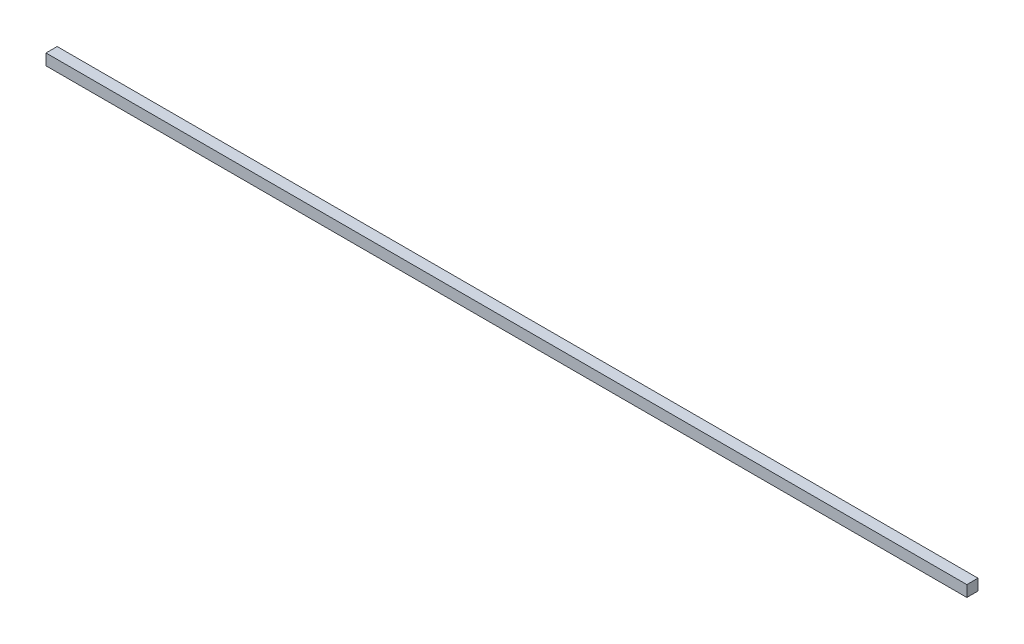
SolidWorks part; units mm, degrees
ref_plane "Front Plane" through (0, 0, 0) normal (0, 0, 1) x (1, 0, 0)
ref_plane "Top Plane" through (0, 0, 0) normal (0, 1, 0) x (1, 0, 0)
ref_plane "Right Plane" through (0, 0, 0) normal (1, 0, 0) x (0, 0, -1)
other "Configuration Table"
sketch "Sketch1" plane through (0, 0, 0) normal (0, 0, 1) x (1, 0, 0)
  line L1 (20, 742) -> (680, 742)
  line L2 (20, 742) -> (20, 750)
  line L3 (20, 750) -> (680, 750)
  line L4 (680, 742) -> (680, 750)
extrude "TOPPING_klape_kat3_pivot_mil_1" add sketch "Sketch1" along normal blind 8 from offset 22 separate body
